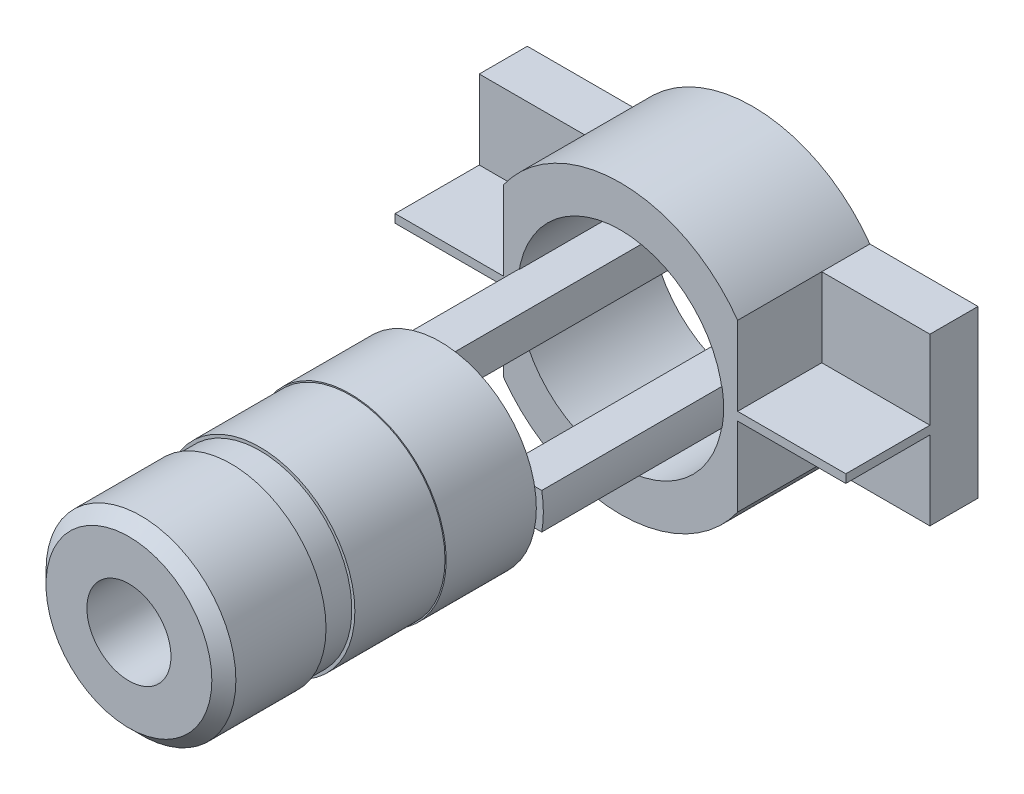
SolidWorks part; units mm, degrees
material "ASTM A36 Steel"
ref_plane "Front Plane" through (0, 0, 0) normal (0, 0, 1) x (1, 0, 0)
ref_plane "Top Plane" through (0, 0, 0) normal (0, 1, 0) x (1, 0, 0)
ref_plane "Right Plane" through (0, 0, 0) normal (1, 0, 0) x (0, 0, -1)
sketch "Sketch1" plane through (0, 0, 0) normal (0, 0, 1) x (1, 0, 0)
  circle A0 centre (0, 0) radius 7.9
  circle A1 centre (0, 0) radius 3.5
  dimension "D1" = 15.8
  dimension "D2" = 7
extrude "Boss-Extrude1" add sketch "Sketch1" along normal blind 18.4
chamfer "Chamfer1" distance 1 angle 45 1 edges at (7.9, 0, 18.4)
ref_plane "Plane7" [suppressed] through (0, 0, 7.5) normal (0, 0, -1) x (-1, 0, 0)
ref_plane "Plane8" through (0, 0, 9.9) normal (0, 0, -1) x (-1, 0, 0)
sketch "Sketch19" plane through (0, 0, 9.9) normal (0, 0, -1) x (-1, 0, 0)
  circle A0 centre (0, 0) radius 7.65
  circle A1 centre (0, 0) radius 7.9
  dimension "D1" = 15.3
extrude "Cut-Extrude6" cut sketch "Sketch19" along normal blind 2.4
sketch "Sketch20" plane through (0, 0, 0) normal (0, 0, -1) x (-1, 0, 0)
  circle A0 centre (0, 0) radius 7.9
  circle A1 centre (0, 0) radius 4.5
  dimension "D1" = 9
extrude "Boss-Extrude3" [suppressed] add sketch "Sketch20" along normal blind 28.6 separate body
sketch "Sketch21" [suppressed] plane through (0, 0, -28.6) normal (0, 0, -1) x (-1, 0, 0)
  line L1 (0, 3.0042) -> (-7.3065, 3.0042)
  line L9 (-7.3081, -3.0004) -> (0, -3.0004)
  line L12 (0, -3.0004) -> (7.3081, -3.0004)
  line L13 (0, 3.0042) -> (7.3065, 3.0042)
  circle A0 centre (0, 0) radius 7.9 construction
  arc A1 (-7.3065, 3.0042) -> (7.3065, 3.0042) centre (0, 0) cw
  arc A2 (-7.3081, -3.0004) -> (7.3081, -3.0004) centre (0, 0) ccw
extrude "Cut-Extrude7" [suppressed] cut sketch "Sketch21" against normal blind 28.6
ref_plane "Plane9" [suppressed] through (0, 0, -28.6) normal (0, 0, -1) x (-1, 0, 0)
sketch "Sketch22" [suppressed] plane through (0, 0, -28.6) normal (0, 0, -1) x (-1, 0, 0)
  circle A0 centre (0, 0) radius 12
  dimension "D1" = 24
extrude "Boss-Extrude4" [suppressed] add sketch "Sketch22" along normal blind 6
sketch "Sketch23" [suppressed] plane through (0, 0, -34.6) normal (0, 0, -1) x (-1, 0, 0)
  circle A0 centre (0, 0) radius 4.5
  dimension "D1" = 9
extrude "Cut-Extrude8" [suppressed] cut sketch "Sketch23" against normal up to next
sketch "Sketch24" plane through (0, 0, 0) normal (0, 0, -1) x (-1, 0, 0)
  circle A0 centre (0, 0) radius 8
  dimension "D1" = 16
extrude "Boss-Extrude5" add sketch "Sketch24" along normal blind 7.5 separate body
sketch "Sketch25" plane through (0, 0, -7.5) normal (0, 0, -1) x (-1, 0, 0)
  line L3 (-5.15, 1.5) -> (-8.45, 1.5)
  line L4 (-5.15, -1.5) -> (-8.45, -1.5)
  line L5 (-0.0834, 0) -> (-5.15, 0) construction
  line L6 (-5.15, 1.5) -> (-5.15, 0)
  line L7 (-5.15, 0) -> (-5.15, -1.5)
  line L8 (0, 8.8) -> (0, -8.8) construction
  line L9 (5.15, 1.5) -> (5.15, 0)
  line L10 (5.15, 1.5) -> (8.45, 1.5)
  line L11 (5.15, -1.5) -> (8.45, -1.5)
  line L12 (5.15, 0) -> (5.15, -1.5)
  arc A0 (8.5834, 0) -> (8.45, 1.5) centre (0.0834, 0) ccw
  arc A1 (-8.5834, 0) -> (-8.45, 1.5) centre (-0.0834, 0) cw
  arc A2 (-8.5834, 0) -> (-8.45, -1.5) centre (-0.0834, 0) ccw
  arc A3 (8.5834, 0) -> (8.45, -1.5) centre (0.0834, 0) cw
  point P2 (-8.4222, 0)
  point P3 (0, 0)
  point P4 (0, 0)
  point P5 (-6.6005, 0)
  dimension "D5" = 8.5
  dimension "D1" = 3.3
  dimension "D2" = 3.3
  dimension "D3" = 3
  dimension "D4" = 5.15
extrude "Boss-Extrude6" add sketch "Sketch25" along normal blind 26 separate body
ref_plane "Plane10" through (0, 0, -33.5) normal (0, 0, -1) x (-1, 0, 0)
sketch "Sketch26" plane through (0, 0, -33.5) normal (0, 0, -1) x (-1, 0, 0)
  circle A0 centre (0, 0) radius 11.95
  circle A1 centre (0, 0) radius 8.55
  dimension "D1" = 23.9
  dimension "D2" = 17.1
extrude "Boss-Extrude7" add sketch "Sketch26" against normal blind 11 separate body
sketch "Sketch27" plane through (0, 0, -22.5) normal (0, 0, 1) x (1, 0, 0)
  line L2 (-9.75, 0) -> (-9.75, 6.9094)
  line L3 (-9.75, 0) -> (-9.75, -6.9094)
  line L4 (9.75, 0) -> (9.75, 6.9094)
  line L5 (9.75, 0) -> (9.75, -6.9094)
  circle A0 centre (0, 0) radius 11.95 construction
  arc A1 (-9.75, 6.9094) -> (-9.75, -6.9094) centre (0, 0) ccw
  arc A2 (9.75, 6.9094) -> (9.75, -6.9094) centre (0, 0) cw
extrude "Cut-Extrude9" cut sketch "Sketch27" against normal through all
sketch "Sketch28" plane through (0, 0, -7.5) normal (0, 0, -1) x (-1, 0, 0)
  circle A0 centre (0, 0) radius 3.5
  dimension "D1" = 7
extrude "Cut-Extrude10" cut sketch "Sketch28" against normal through all
sketch "Sketch29" plane through (-9.75, 0, 0) normal (-1, 0, 0) x (0, 0, 1)
  line L0 (-33.5, 6.9094) -> (-29.5, 6.9094)
  line L1 (-33.5, 6.9094) -> (-22.5, 6.9094) construction
  line L2 (-29.5, 6.9094) -> (-29.5, -6.9094)
  line L3 (-33.5, -6.9094) -> (-22.5, -6.9094) construction
  line L4 (-29.5, -6.9094) -> (-33.5, -6.9094)
  line L5 (-33.5, -6.9094) -> (-33.5, 6.9094)
  dimension "D1" = 4
extrude "Boss-Extrude8" add sketch "Sketch29" along normal blind 9
sketch "Sketch30" plane through (9.75, 0, 0) normal (1, 0, 0) x (0, 0, -1)
  line L0 (33.5, 6.9094) -> (29.5, 6.9094)
  line L1 (33.5, 6.9094) -> (22.5, 6.9094) construction
  line L2 (29.5, 6.9094) -> (29.5, -6.9094)
  line L3 (33.5, -6.9094) -> (22.5, -6.9094) construction
  line L4 (29.5, -6.9094) -> (33.5, -6.9094)
  line L5 (33.5, -6.9094) -> (33.5, 6.9094)
  dimension "D1" = 4
extrude "Boss-Extrude9" add sketch "Sketch30" along normal blind 9
sketch "Sketch31" plane through (9.75, 0, 0) normal (1, 0, 0) x (0, 0, -1)
  line L0 (22.5, 0) -> (22.5, 0.35)
  line L1 (22.5, 6.9094) -> (22.5, -6.9094) construction
  line L2 (22.5, 0.35) -> (29.5, 0.35)
  line L3 (29.5, 6.9094) -> (29.5, -6.9094) construction
  line L4 (22.5, 0) -> (22.5, -0.35)
  line L5 (22.5, -0.35) -> (29.5, -0.35)
  line L6 (29.5, 6.9094) -> (29.5, -6.9094) construction
  line L7 (29.5, 0.35) -> (29.5, -0.35)
  dimension "D1" = 0.35
  dimension "D2" = 0.35
extrude "Boss-Extrude10" add sketch "Sketch31" along normal blind 9
sketch "Sketch32" plane through (-9.75, 0, 0) normal (-1, 0, 0) x (0, 0, 1)
  line L0 (-22.5, 0) -> (-22.5, 0.35)
  line L1 (-22.5, -6.9094) -> (-22.5, 6.9094) construction
  line L2 (-22.5, 0) -> (-22.5, -0.35)
  line L3 (-22.5, 0.35) -> (-29.5, 0.35)
  line L4 (-29.5, -6.9094) -> (-29.5, 6.9094) construction
  line L5 (-22.5, -0.35) -> (-29.5, -0.35)
  line L6 (-29.5, -6.9094) -> (-29.5, 6.9094) construction
  line L7 (-29.5, 0.35) -> (-29.5, -0.35)
  dimension "D1" = 0.35
  dimension "D2" = 0.35
extrude "Boss-Extrude11" add sketch "Sketch32" along normal blind 9
equation "\"D2@Sketch25\"=\"D1@Sketch25\""
